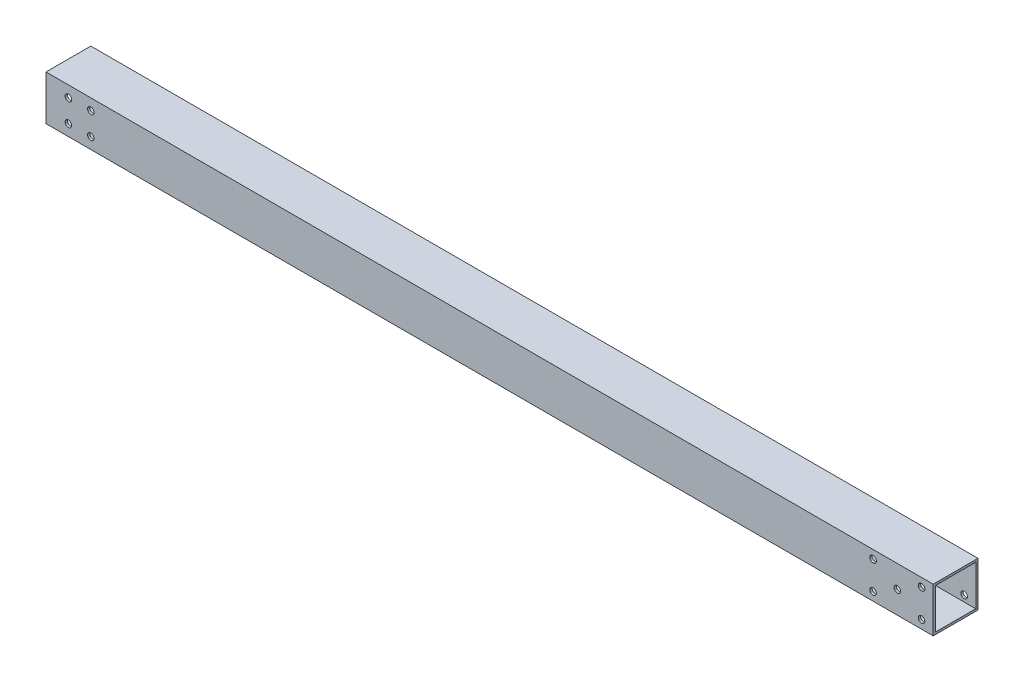
SolidWorks part; units mm, degrees
material "Thornel Mat VMA"
ref_plane "前视基准面" through (0, 0, 0) normal (0, 0, 1) x (1, 0, 0)
ref_plane "上视基准面" through (0, 0, 0) normal (0, 1, 0) x (1, 0, 0)
ref_plane "右视基准面" through (0, 0, 0) normal (1, 0, 0) x (0, 0, -1)
other "Configuration Table"
sketch "草图1" plane through (0, 0, 0) normal (1, 0, 0) x (0, 0, -1)
  line L1 (-9, 9) -> (9, 9)
  line L2 (-9, 9) -> (-9, -9)
  line L3 (-9, -9) -> (9, -9)
  line L4 (9, 9) -> (9, -9)
  line L5 (-9, 9) -> (9, -9) construction
  line L6 (-9, -9) -> (9, 9) construction
  line L7 (-10, 10) -> (10, 10)
  line L8 (-10, 10) -> (-10, -10)
  line L9 (-10, -10) -> (10, -10)
  line L10 (10, 10) -> (10, -10)
  line L11 (-10, 10) -> (10, -10) construction
  line L12 (-10, -10) -> (10, 10) construction
  point P0 (0, 0)
  point P6 (0, 0)
  dimension "D1" = 18
  dimension "D2" = 20
  dimension "D3" = 18
  dimension "D4" = 20
extrude "凸台-拉伸1" add sketch "草图1" along normal blind 396
sketch "草图2" plane through (0, 0, -10) normal (0, 0, -1) x (-1, 0, 0)
  line L0 (-396, -10) -> (-396, 10) construction
  line L2 (-380, 0) -> (-396, 0) construction
  circle A2 centre (-380, 0) radius 12.5 construction
  circle A3 centre (-380, -12.5) radius 1.45
  circle A4 centre (-390.8253, -6.25) radius 1.45
  circle A5 centre (-390.8253, 6.25) radius 1.45
  circle A6 centre (-380, 12.5) radius 1.45
  circle A7 centre (-369.1747, 6.25) radius 1.45
  circle A8 centre (-369.1747, -6.25) radius 1.45
  circle A9 centre (-380, 0) radius 1.45
  dimension "D1" = 25
  dimension "D2" = 2.9
  dimension "D3" = 16
  dimension "D4" = 6
extrude "切除-拉伸1" cut sketch "草图2" against normal through all
sketch "草图3" plane through (0, 0, 10) normal (0, 0, 1) x (1, 0, 0)
  line L0 (396, 10) -> (396, -10) construction
  line L1 (396, 10) -> (0, 10) construction
  line L2 (0, 10) -> (0, -10) construction
  circle A0 centre (10, 5) radius 1.45
  circle A1 centre (20, 5) radius 1.45
  circle A2 centre (10, -5) radius 1.45
  circle A3 centre (20, -5) radius 1.45
  circle A4 centre (369.1747, 6.25) radius 1.45
  circle A5 centre (380, 0) radius 1.45
  circle A6 centre (369.1747, -6.25) radius 1.45
  circle A7 centre (390.8253, -6.25) radius 1.45
  circle A8 centre (390.8253, 6.25) radius 1.45
  dimension "D1" = 2.9
  dimension "D2" = 5.1747
  dimension "D3" = 26.8253
  dimension "D4" = 3.75
  dimension "D5" = 10
  dimension "D6" = 16
  dimension "D7" = 5
  dimension "D8" = 10
  dimension "D9" = 20
  dimension "D10" = 396
extrude "切除-拉伸2" cut sketch "草图3" against normal through all
